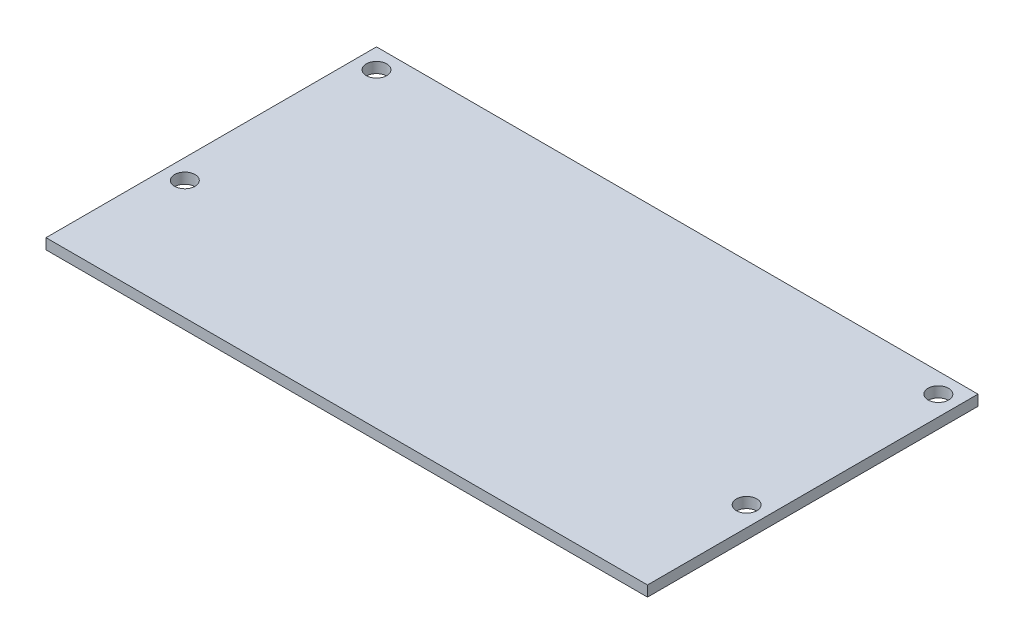
SolidWorks part; units mm, degrees
ref_plane "前视基准面" through (0, 0, 0) normal (0, 0, 1) x (1, 0, 0)
ref_plane "上视基准面" through (0, 0, 0) normal (0, 1, 0) x (1, 0, 0)
ref_plane "右视基准面" through (0, 0, 0) normal (1, 0, 0) x (0, 0, -1)
sketch "草图1" plane through (0, 0, 0) normal (0, 1, 0) x (1, 0, 0)
  line L1 (-45.5, 25) -> (45.5, 25)
  line L2 (-45.5, 25) -> (-45.5, -25)
  line L3 (-45.5, -25) -> (45.5, -25)
  line L4 (45.5, 25) -> (45.5, -25)
  line L5 (-45.5, 25) -> (45.5, -25) construction
  line L6 (-45.5, -25) -> (45.5, 25) construction
  line L7 (-42.5, 22) -> (42.5, 22) construction
  line L8 (-42.5, 22) -> (-42.5, -7) construction
  line L9 (-42.5, -7) -> (42.5, -7) construction
  line L10 (42.5, 22) -> (42.5, -7) construction
  line L11 (-42.5, 22) -> (42.5, -7) construction
  line L12 (-42.5, -7) -> (42.5, 22) construction
  circle A0 centre (-42.5, -7) radius 1.55
  circle A1 centre (-42.5, 22) radius 1.55
  circle A2 centre (42.5, 22) radius 1.55
  circle A3 centre (42.5, -7) radius 1.55
  point P0 (0, 0)
  point P6 (0, 7.5)
  dimension "D5" = 3.1
  dimension "D6" = 3.1
  dimension "D7" = 3.1
  dimension "D8" = 3.1
  dimension "D9" = 3
  dimension "D10" = 3
  dimension "D1" = 50
  dimension "D2" = 91
  dimension "D3" = 29
  dimension "D4" = 85
extrude "凸台-拉伸1" add sketch "草图1" along normal blind 1.6
